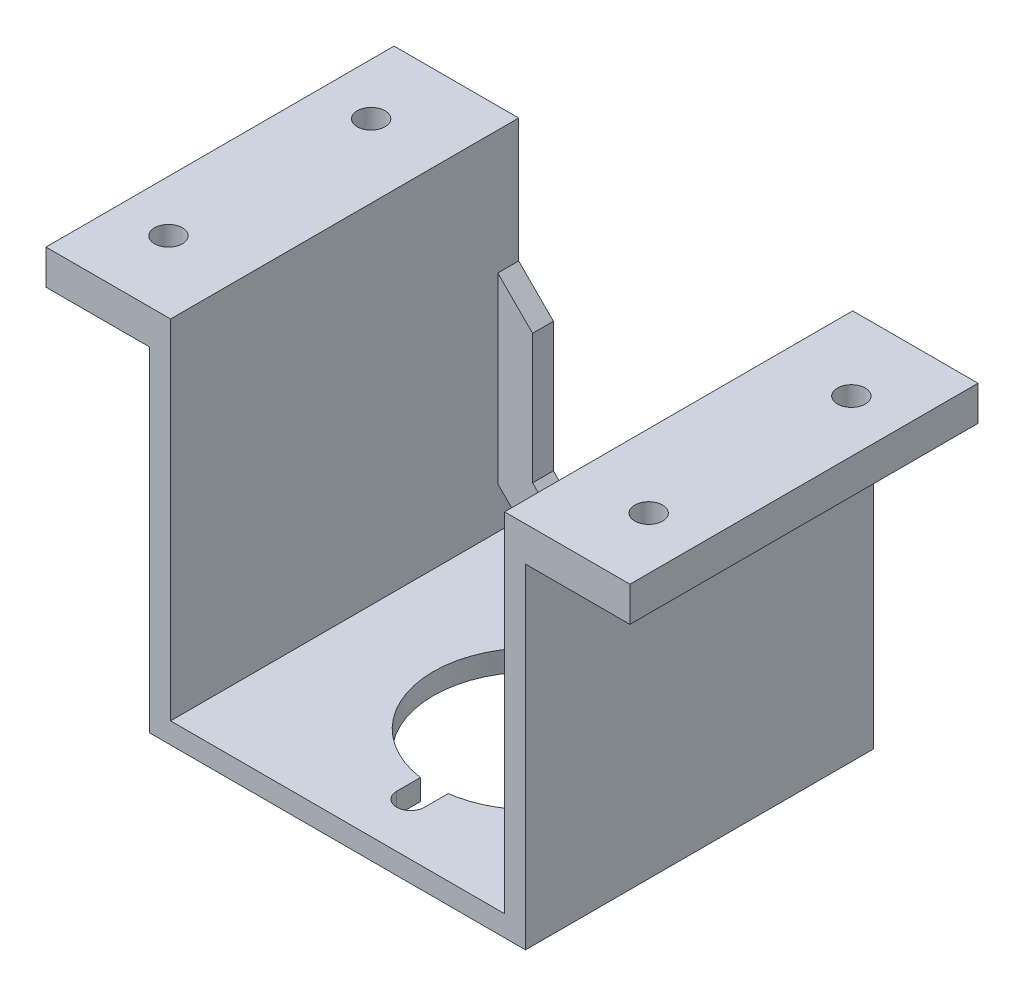
SolidWorks part; units mm, degrees
ref_plane "Front Plane" through (0, 0, 0) normal (0, 0, 1) x (1, 0, 0)
ref_plane "Top Plane" through (0, 0, 0) normal (0, 1, 0) x (1, 0, 0)
ref_plane "Right Plane" through (0, 0, 0) normal (1, 0, 0) x (0, 0, -1)
sketch "Sketch1" plane through (0, 0, 0) normal (0, 1, 0) x (1, 0, 0)
  line L1 (-23.0791, 14.3848) -> (26.9209, 14.3848)
  line L2 (-23.0791, 14.3848) -> (-23.0791, -25.6152)
  line L3 (-23.0791, -25.6152) -> (26.9209, -25.6152)
  line L4 (26.9209, 14.3848) -> (26.9209, -25.6152)
  dimension "D1" = 50
  dimension "D2" = 40
extrude "Boss-Extrude1" add sketch "Sketch1" along normal blind 3
sketch "Sketch2" plane through (0, 3, 0) normal (0, 1, 0) x (1, 0, 0)
  line L0 (-19.0791, 14.3848) -> (-19.0791, -25.6152)
  line L1 (26.9209, 14.3848) -> (-23.0791, 14.3848) construction
  line L2 (-23.0791, -25.6152) -> (26.9209, -25.6152) construction
  line L7 (-23.0791, 14.3848) -> (-23.0791, -25.6152)
  line L8 (-23.0791, -25.6152) -> (26.9209, -25.6152)
  line L9 (26.9209, -25.6152) -> (26.9209, 14.3848)
  line L10 (26.9209, 14.3848) -> (-23.0791, 14.3848)
  line L11 (-23.0791, 14.3848) -> (-23.0791, -25.6152)
  line L12 (-23.0791, -25.6152) -> (-19.0791, -25.6152)
  line L14 (-19.0791, 14.3848) -> (-23.0791, 14.3848)
  dimension "D1" = 0
  dimension "D2" = 4
sketch "Sketch5" plane through (0, 3, 0) normal (0, 1, 0) x (1, 0, 0)
  line L0 (24.9209, 14.3848) -> (24.9209, -25.6152)
  line L1 (26.9209, 14.3848) -> (-23.0791, 14.3848) construction
  line L2 (-23.0791, -25.6152) -> (26.9209, -25.6152) construction
  line L7 (-23.0791, 14.3848) -> (-23.0791, -25.6152)
  line L8 (-23.0791, -25.6152) -> (26.9209, -25.6152)
  line L9 (26.9209, -25.6152) -> (26.9209, 14.3848)
  line L10 (26.9209, 14.3848) -> (-23.0791, 14.3848)
  line L12 (24.9209, -25.6152) -> (26.9209, -25.6152)
  line L13 (26.9209, -25.6152) -> (26.9209, 14.3848)
  line L14 (26.9209, 14.3848) -> (24.9209, 14.3848)
  line L15 (-23.0791, 14.3848) -> (-23.0791, -25.6152)
  dimension "D1" = 0
  dimension "D2" = 2
sketch "Sketch6" plane through (0, 0, 0) normal (0, -1, 0) x (1, 0, 0)
  line L0 (-23.0791, 5.6152) -> (-1.0791, 5.6152)
  line L1 (-23.0791, -14.3848) -> (-23.0791, 25.6152) construction
  line L2 (6.9209, 5.6152) -> (6.9209, -11.8848)
  line L3 (-1.0791, 5.6152) -> (6.9209, 5.6152)
  line L4 (6.9209, 5.6152) -> (6.9209, 23.1152)
  line L5 (24.4209, 13.0152) -> (18.923, 13.0152)
  line L6 (6.9209, 5.6152) -> (24.4209, 5.6152)
  line L7 (24.4209, 5.6152) -> (24.4209, 13.0152)
  line L8 (24.4209, 5.6152) -> (24.4209, -1.7848)
  line L9 (24.4209, -1.7848) -> (18.923, -1.7848)
  arc A1 (18.923, 13.0152) -> (18.923, -1.7848) centre (6.9209, 5.6152) ccw
  circle A2 centre (6.9209, 23.1152) radius 2
  circle A3 centre (6.9209, -11.8848) radius 2
  dimension "D2" = 8
  dimension "D3" = 17.5
  dimension "D5" = 17.5
  dimension "D1" = 22
  dimension "D4" = 17.5
extrude "Cut-Extrude9" cut sketch "Sketch6" against normal blind 5
sketch "Sketch9" plane through (0, 0, 25.6152) normal (0, 0, 1) x (1, 0, 0)
sketch "Sketch16" plane through (24.4209, 0, 0) normal (-1, 0, 0) x (0, 0, 1)
  line L1 (13.0152, 0) -> (-1.7848, 0)
  line L2 (13.0152, 0) -> (13.0152, 3)
  line L3 (13.0152, 3) -> (-1.7848, 3)
  line L4 (-1.7848, 0) -> (-1.7848, 3)
extrude "Cut-Extrude10" cut sketch "Sketch16" against normal blind 0.5
sketch "Sketch21" plane through (0, 0, 0) normal (0, -1, 0) x (-1, 0, 0)
  circle A0 centre (-6.9209, -5.6152) radius 14.25
extrude "Cut-Extrude15" cut sketch "Sketch21" against normal blind 4
sketch "Sketch22" plane through (0, 3, 0) normal (0, 1, 0) x (1, 0, 0)
  line L0 (24.9209, 4.1848) -> (17.2661, 4.1848)
  line L1 (24.9209, -15.4152) -> (17.2661, -15.4152)
  line L2 (19.0989, 1.7848) -> (24.9209, 1.7848) construction
  line L3 (19.0989, -13.0152) -> (24.9209, -13.0152) construction
  circle A0 centre (6.9209, -5.6152) radius 15.9999
  arc A1 (19.0989, 1.7848) -> (19.0989, -13.0152) centre (6.9209, -5.6152) ccw construction
  arc M4 (19.0989, -13.0152) -> (19.0989, 1.7848) centre (6.9209, -5.6152) cw
  line M5 (19.0989, 1.7848) -> (24.9209, 1.7848)
  line M7 (24.9209, -13.0152) -> (19.0989, -13.0152)
  dimension "D1" = 2.4
  dimension "D2" = 2.4
extrude "Cut-Extrude16" cut sketch "Sketch22" against normal blind 4 contours A0 L0 M5 M4 | L1 A0 M7 M4
sketch "Sketch33" plane through (0, 3, 0) normal (0, 1, 0) x (1, 0, 0)
  line L0 (4.9209, 11.8848) -> (4.9209, -23.1152)
  line L1 (8.9209, -23.1152) -> (8.9209, 11.8848)
  line L2 (4.9209, 11.8848) -> (8.9209, 11.8848)
  line L3 (4.9209, -23.1152) -> (8.9209, -23.1152)
  circle A0 centre (6.9209, 11.8848) radius 2 construction
  circle A1 centre (6.9209, -23.1152) radius 2 construction
extrude "Cut-Extrude23" cut sketch "Sketch33" against normal blind 5
sketch "Sketch34" plane through (0, 0, -14.3848) normal (0, 0, -1) x (-1, 0, 0)
  line L0 (55, 0) -> (-55, 0) construction
  line L1 (-26.9209, 3) -> (23.066, 3)
  line L2 (-26.9209, 3) -> (-26.9209, 0)
  line L3 (-26.9209, 0) -> (23.066, 0)
  line L4 (23.066, 3) -> (23.066, 0)
extrude "Boss-Extrude2" add sketch "Sketch34" along normal blind 3
sketch "Sketch35" plane through (0, 0, 25.6152) normal (0, 0, 1) x (1, 0, 0)
  line L0 (55, 0) -> (-55, 0) construction
  line L1 (-23.0791, 3) -> (26.9209, 3)
  line L2 (-23.0791, 3) -> (-23.0791, 0)
  line L3 (-23.0791, 0) -> (26.9209, 0)
  line L4 (26.9209, 3) -> (26.9209, 0)
  line L5 (26.9209, 3) -> (26.9209, 0) construction
extrude "Boss-Extrude3" add sketch "Sketch35" along normal blind 3
sketch "Sketch36" plane through (26.9209, 0, 0) normal (1, 0, 0) x (0, 0, -1)
  line L0 (55, 0) -> (-55, 0) construction
  line L1 (-28.6152, 3) -> (17.3848, 3)
  line L2 (-28.6152, 3) -> (-28.6152, 0)
  line L3 (-28.6152, 0) -> (17.3848, 0)
  line L4 (17.3848, 3) -> (17.3848, 0)
  line L5 (17.3848, 3) -> (17.3848, 0) construction
extrude "Boss-Extrude4" add sketch "Sketch36" along normal blind 4
sketch "Sketch38" plane through (0, 3, 0) normal (0, 1, 0) x (1, 0, 0)
  line L0 (30.9209, -28.6152) -> (-23.0791, -28.6152) construction
  line L1 (30.9209, 17.3848) -> (27.9209, 17.3848)
  line L2 (30.9209, 17.3848) -> (30.9209, -28.6152)
  line L3 (30.9209, -28.6152) -> (27.9209, -28.6152)
  line L4 (27.9209, 17.3848) -> (27.9209, -28.6152)
  line L6 (-23.066, 17.3848) -> (-20.066, 17.3848)
  line L7 (-23.066, 17.3848) -> (-23.066, -28.6152)
  line L8 (-23.066, -28.6152) -> (-20.066, -28.6152)
  line L9 (-20.066, 17.3848) -> (-20.066, -28.6152)
  dimension "D1" = 3
  dimension "D2" = 3
extrude "Boss-Extrude5" add sketch "Sketch38" along normal blind 25
sketch "Sketch39" plane through (-23.066, 0, 0) normal (-1, 0, 0) x (0, 0, 1)
  line L1 (-17.3848, 28) -> (28.1507, 28)
  line L2 (-17.3848, 28) -> (-17.3848, 25)
  line L3 (-17.3848, 25) -> (28.1507, 25)
  line L4 (28.1507, 28) -> (28.1507, 25)
  dimension "D1" = 3
extrude "Boss-Extrude6" add sketch "Sketch39" along normal blind 15
sketch "Sketch40" plane through (30.9209, 0, 0) normal (1, 0, 0) x (0, 0, -1)
  line L0 (17.3848, 0) -> (17.3848, 28) construction
  line L1 (-28.6152, 28) -> (17.3848, 28)
  line L2 (-28.6152, 28) -> (-28.6152, 25)
  line L3 (-28.6152, 25) -> (17.3848, 25)
  line L4 (17.3848, 28) -> (17.3848, 25)
  dimension "D1" = 3
extrude "Boss-Extrude7" add sketch "Sketch40" along normal blind 15
sketch "Sketch41" plane through (-23.066, 0, 0) normal (-1, 0, 0) x (0, 0, 1)
  line L1 (28.6152, 28) -> (28.1507, 28)
  line L2 (28.6152, 28) -> (28.6152, 25)
  line L3 (28.6152, 25) -> (28.1507, 25)
  line L4 (28.1507, 28) -> (28.1507, 25)
extrude "Boss-Extrude8" add sketch "Sketch41" along normal blind 15
sketch "Sketch42" plane through (0, 25, 0) normal (0, -1, 0) x (1, 0, 0)
  line L0 (38.4209, 28.6152) -> (38.4209, -17.3848) construction
  line L1 (45.9209, 28.6152) -> (30.9209, 28.6152) construction
  line L2 (45.9209, -17.3848) -> (30.9209, -17.3848) construction
  line L3 (45.9209, 5.6152) -> (30.9209, -17.3848) construction
  line L4 (45.9209, 28.6152) -> (45.9209, -17.3848) construction
  line L5 (30.9209, 28.6152) -> (45.9209, 5.6152) construction
  line L6 (45.9209, 28.6152) -> (30.9209, 12.2239) construction
  line L7 (30.9209, 28.6152) -> (30.9209, -17.3848) construction
  line L8 (45.9209, -17.3848) -> (30.9209, 0) construction
  line L9 (44.2539, 0) -> (-44.2539, 0) construction
  circle A0 centre (38.4209, 20.4195) radius 2
  circle A2 centre (38.4209, -8.6924) radius 2
  dimension "D1" = 4
  dimension "D2" = 4
extrude "Cut-Extrude24" cut sketch "Sketch42" against normal blind 15 contours A0 | A2
sketch "Sketch43" plane through (0, 25, 0) normal (0, -1, 0) x (1, 0, 0)
  line L0 (-30.566, 28.6152) -> (-30.566, -17.3848) construction
  line L1 (-38.066, 28.6152) -> (-23.066, 28.6152) construction
  line L2 (-38.066, -17.3848) -> (-23.066, -17.3848) construction
  line L3 (40.4209, 20.4195) -> (-49.3024, 20.4195) construction
  line L4 (40.4209, -8.6924) -> (-52.4667, -8.6924) construction
  circle A0 centre (38.4209, 20.4195) radius 2 construction
  circle A1 centre (38.4209, -8.6924) radius 2 construction
  circle A2 centre (-30.566, 20.4195) radius 2
  circle A3 centre (-30.566, -8.6924) radius 2
  dimension "D1" = 4
extrude "Cut-Extrude25" cut sketch "Sketch43" against normal blind 15
sketch "Sketch44" plane through (0, 25, 0) normal (0, -1, 0) x (1, 0, 0)
  line L1 (-23.0791, 28.6152) -> (-38.066, 28.6152)
  line L2 (-23.0791, 28.6152) -> (-23.0791, -17.3848)
  line L3 (-23.0791, -17.3848) -> (-38.066, -17.3848)
  line L4 (-38.066, 28.6152) -> (-38.066, -17.3848)
  line L8 (-23.066, -17.3848) -> (-23.066, 28.6152)
  line L9 (-23.066, 28.6152) -> (-38.066, 28.6152)
  line L10 (-38.066, 28.6152) -> (-38.066, -17.3848)
  line L11 (-38.066, -17.3848) -> (-23.066, -17.3848)
  line L12 (-23.066, -17.3848) -> (-23.066, 28.6152)
  line L13 (-23.066, 28.6152) -> (-38.066, 28.6152)
  line L14 (-38.066, 28.6152) -> (-38.066, -17.3848)
  line L15 (-38.066, -17.3848) -> (-23.066, -17.3848)
  circle M9 centre (-30.566, 20.4195) radius 2
  circle M10 centre (-30.566, -8.6924) radius 2
  line M12 (-23.066, 28.6152) -> (-38.066, 28.6152)
  line M13 (-38.066, 28.6152) -> (-38.066, -17.3848)
  line M14 (-38.066, -17.3848) -> (-23.066, -17.3848)
  dimension "D1" = 0
extrude "Boss-Extrude10" add sketch "Sketch44" along normal blind 1 contours L2 M12 M13 M14 M10 M9
sketch "Sketch46" plane through (0, 25, 0) normal (0, -1, 0) x (1, 0, 0)
  line L1 (45.9209, 28.6152) -> (30.9209, 28.6152)
  line L2 (45.9209, 28.6152) -> (45.9209, -17.3848)
  line L3 (45.9209, -17.3848) -> (30.9209, -17.3848)
  line L4 (30.9209, 28.6152) -> (30.9209, -17.3848)
  line L8 (30.9209, 28.6152) -> (30.9209, -17.3848)
  line L9 (30.9209, -17.3848) -> (45.9209, -17.3848)
  line L10 (45.9209, -17.3848) -> (45.9209, 28.6152)
  line L11 (45.9209, 28.6152) -> (30.9209, 28.6152)
  line L12 (30.9209, 28.6152) -> (30.9209, -17.3848)
  line L13 (30.9209, -17.3848) -> (45.9209, -17.3848)
  line L14 (45.9209, -17.3848) -> (45.9209, 28.6152)
  line L15 (45.9209, 28.6152) -> (30.9209, 28.6152)
  line L16 (45.9209, 28.6152) -> (27.9209, 28.6152)
  line L17 (45.9209, -17.3848) -> (45.9209, 28.6152)
  line L18 (27.9209, -17.3848) -> (45.9209, -17.3848)
  line L19 (27.9209, 28.6152) -> (27.9209, -17.3848)
  line L20 (45.9209, 28.6152) -> (27.9209, 28.6152)
  line L21 (45.9209, -17.3848) -> (45.9209, 28.6152)
  line L22 (27.9209, -17.3848) -> (45.9209, -17.3848)
  line L23 (27.9209, 28.6152) -> (27.9209, -17.3848)
  circle M13 centre (38.4209, 20.4195) radius 2
  circle M14 centre (38.4209, -8.6924) radius 2
  line M15 (30.9209, 28.6152) -> (30.9209, -17.3848)
  line M16 (30.9209, -17.3848) -> (45.9209, -17.3848)
  line M17 (45.9209, -17.3848) -> (45.9209, 28.6152)
  line M18 (45.9209, 28.6152) -> (30.9209, 28.6152)
  dimension "D1" = 0
  dimension "D2" = 0
extrude "Boss-Extrude11" add sketch "Sketch46" along normal blind 1 contours M18 M15 M16 M17 M14 M13
sketch "Sketch47" plane through (0, 0, -17.3848) normal (0, 0, -1) x (-1, 0, 0)
  line L0 (55, 0) -> (-55, 0) construction
  line L1 (-45.9209, 28) -> (37.9603, 28)
  line L2 (-45.9209, 28) -> (-45.9209, 0)
  line L3 (-45.9209, 0) -> (37.9603, 0)
  line L4 (37.9603, 28) -> (37.9603, 0)
  line L19 (23.066, 0) -> (23.066, 25)
  line L20 (23.066, 25) -> (23.0791, 25)
  line L21 (-30.9209, 24) -> (-30.9209, 0)
  line L22 (-45.9209, 24) -> (-30.9209, 24)
  line L23 (-45.9209, 28) -> (-45.9209, 24)
  line L24 (-27.9209, 28) -> (-45.9209, 28)
  line L25 (-27.9209, 3) -> (-27.9209, 28)
  line L26 (20.066, 3) -> (-27.9209, 3)
  line L27 (20.066, 28) -> (20.066, 3)
  line L28 (38.066, 28) -> (20.066, 28)
  line L29 (23.066, 25) -> (23.0791, 25)
  line L30 (38.066, 24) -> (38.066, 28)
  line L31 (38.066, 24) -> (38.066, 28)
  line L32 (23.0791, 24) -> (38.066, 24)
  line L33 (23.066, 3) -> (23.066, 25)
  line L34 (23.0791, 3) -> (23.066, 3)
  line L35 (23.0791, 0) -> (23.0791, 3)
  line L36 (-30.9209, 0) -> (23.0791, 0)
  line L37 (-30.9209, 24) -> (-30.9209, 0)
  line L38 (-45.9209, 24) -> (-30.9209, 24)
  line L39 (-45.9209, 28) -> (-45.9209, 24)
  line L40 (-27.9209, 28) -> (-45.9209, 28)
  line L41 (-27.9209, 3) -> (-27.9209, 28)
  line L42 (20.066, 3) -> (-27.9209, 3)
  line L43 (20.066, 28) -> (20.066, 3)
  line L44 (38.066, 28) -> (20.066, 28)
  line L49 (23.066, 3) -> (23.066, 25)
  line L50 (23.0791, 3) -> (23.066, 3)
  line L51 (23.0791, 0) -> (23.0791, 3)
  line L52 (-30.9209, 0) -> (23.0791, 0)
  line L53 (23.0791, 24) -> (38.066, 24)
  line L54 (23.0791, 25) -> (23.0791, 24)
  line L55 (23.0791, 25) -> (23.0791, 24)
  line L56 (38.066, 28) -> (20.066, 28)
  line L57 (20.066, 28) -> (20.066, 3)
  line L58 (20.066, 3) -> (-27.9209, 3)
  line L59 (-27.9209, 3) -> (-27.9209, 28)
  line L60 (-27.9209, 28) -> (-45.9209, 28)
  line L61 (-45.9209, 28) -> (-45.9209, 24)
  line L62 (-45.9209, 24) -> (-30.9209, 24)
  line L63 (-30.9209, 24) -> (-30.9209, 0)
  line L64 (-30.9209, 0) -> (23.066, 0)
  line L65 (23.066, 0) -> (23.066, 25)
  line L66 (23.066, 25) -> (23.0791, 25)
  line L67 (23.066, 25) -> (23.0791, 25)
  line L68 (23.0791, 25) -> (23.0791, 24)
  line L69 (23.0791, 25) -> (23.0791, 24)
  line L70 (38.066, 28) -> (20.066, 28)
  line L71 (20.066, 28) -> (20.066, 3)
  line L72 (20.066, 3) -> (-27.9209, 3)
  line L73 (-27.9209, 3) -> (-27.9209, 28)
  line L74 (-27.9209, 28) -> (-45.9209, 28)
  line L75 (-45.9209, 28) -> (-45.9209, 24)
  line L76 (-45.9209, 24) -> (-30.9209, 24)
  line L77 (-30.9209, 24) -> (-30.9209, 0)
  line L78 (-30.9209, 0) -> (23.066, 0)
  line L79 (23.0791, 24) -> (38.066, 24)
  line L80 (23.0791, 24) -> (38.066, 24)
  line L81 (38.066, 24) -> (38.066, 28)
  line L82 (38.066, 24) -> (38.066, 28)
  line M35 (23.066, 0) -> (23.066, 25)
  line M36 (23.066, 25) -> (23.0791, 25)
  line M37 (23.0791, 25) -> (23.0791, 24)
  line M38 (23.0791, 24) -> (38.066, 24)
  line M40 (38.066, 28) -> (20.066, 28)
  line M41 (20.066, 28) -> (20.066, 3)
  line M42 (20.066, 3) -> (-27.9209, 3)
  line M43 (-27.9209, 3) -> (-27.9209, 28)
  line M44 (-27.9209, 28) -> (-45.9209, 28)
  line M45 (-45.9209, 28) -> (-45.9209, 24)
  line M46 (-45.9209, 24) -> (-30.9209, 24)
  line M47 (-30.9209, 24) -> (-30.9209, 0)
  line M48 (-30.9209, 0) -> (23.066, 0)
  dimension "D1" = 0
  dimension "D2" = 0
extrude "Boss-Extrude12" add sketch "Sketch47" along normal blind 2 contours L4 M40 M41 M42 M43 M44 M45 M46 M47 M48 M35 M36 M37 M38
sketch "Sketch48" plane through (0, 0, 28.6152) normal (0, 0, 1) x (1, 0, 0)
  line L0 (55, 0) -> (-55, 0) construction
  line L1 (-38.066, 28) -> (45.9209, 28)
  line L2 (-38.066, 28) -> (-38.066, 0)
  line L3 (-38.066, 0) -> (45.9209, 0)
  line L4 (45.9209, 28) -> (45.9209, 0)
  line L19 (-37.9603, 28) -> (-37.9603, 24)
  line L20 (-20.066, 28) -> (-37.9603, 28)
  line L21 (-20.066, 3) -> (-20.066, 28)
  line L22 (27.9209, 3) -> (-20.066, 3)
  line L23 (27.9209, 28) -> (27.9209, 3)
  line L24 (45.9209, 28) -> (27.9209, 28)
  line L25 (45.9209, 24) -> (45.9209, 28)
  line L26 (30.9209, 24) -> (45.9209, 24)
  line L27 (30.9209, 0) -> (30.9209, 24)
  line L28 (-23.066, 0) -> (30.9209, 0)
  line L29 (-23.066, 25) -> (-23.066, 0)
  line L30 (-23.0791, 25) -> (-23.066, 25)
  line L31 (-23.0791, 24) -> (-23.0791, 25)
  line L32 (-37.9603, 24) -> (-23.0791, 24)
  line L33 (-37.9603, 28) -> (-37.9603, 24)
  line L34 (-20.066, 28) -> (-37.9603, 28)
  line L35 (-20.066, 3) -> (-20.066, 28)
  line L36 (27.9209, 3) -> (-20.066, 3)
  line L37 (27.9209, 28) -> (27.9209, 3)
  line L38 (45.9209, 28) -> (27.9209, 28)
  line L39 (45.9209, 24) -> (45.9209, 28)
  line L40 (30.9209, 24) -> (45.9209, 24)
  line L41 (30.9209, 0) -> (30.9209, 24)
  line L42 (-23.066, 0) -> (30.9209, 0)
  line L43 (-23.066, 25) -> (-23.066, 0)
  line L44 (-23.0791, 25) -> (-23.066, 25)
  line L45 (-23.0791, 24) -> (-23.0791, 25)
  line L46 (-37.9603, 24) -> (-23.0791, 24)
  line M19 (30.9209, 0) -> (30.9209, 24)
  line M20 (30.9209, 24) -> (45.9209, 24)
  line M21 (45.9209, 24) -> (45.9209, 28)
  line M22 (45.9209, 28) -> (27.9209, 28)
  line M23 (27.9209, 28) -> (27.9209, 3)
  line M24 (27.9209, 3) -> (-20.066, 3)
  line M25 (-20.066, 3) -> (-20.066, 28)
  line M26 (-20.066, 28) -> (-38.066, 28)
  line M28 (-38.066, 24) -> (-23.0791, 24)
  line M29 (-23.0791, 24) -> (-23.0791, 25)
  line M30 (-23.0791, 25) -> (-23.066, 25)
  line M31 (-23.066, 25) -> (-23.066, 3)
  dimension "D1" = 0
extrude "Boss-Extrude13" add sketch "Sketch48" along normal blind 2 contours L43 L3 L33 M31 M19 M20 M21 M22 M23 M24 M25 M26 M28 M29 M30
sketch "Sketch49" plane through (0, 3, 0) normal (0, 1, 0) x (1, 0, 0)
  line L0 (27.9209, 19.3848) -> (27.9209, -30.6152) construction
  line L1 (-20.066, 19.3848) -> (27.9209, 19.3848)
  line L2 (-20.066, 19.3848) -> (-20.066, 17.3848)
  line L3 (-20.066, 17.3848) -> (27.9209, 17.3848)
  line L4 (27.9209, 19.3848) -> (27.9209, 17.3848)
  dimension "D1" = 2
extrude "Boss-Extrude14" add sketch "Sketch49" along normal blind 10
sketch "Sketch50" plane through (0, 0, -17.3848) normal (0, 0, 1) x (1, 0, 0)
  line L0 (-20.066, 13) -> (-9.8306, 2.7646)
  line L1 (27.9209, 13) -> (17.9209, 3)
  line L2 (-20.066, 3) -> (27.9209, 3) construction
  line L3 (27.9209, 13) -> (-20.066, 13)
  line L4 (-9.8306, 2.7646) -> (17.9209, 3)
extrude "Cut-Extrude26" cut sketch "Sketch50" against normal blind 10
sketch "Sketch51" plane through (0, 28, 0) normal (0, 1, 0) x (1, 0, 0)
  line L0 (45.9209, 19.3848) -> (45.9209, -30.6152) construction
  line L1 (-37.9603, 19.3848) -> (45.9209, 19.3848)
  line L2 (-37.9603, 19.3848) -> (-37.9603, -30.6152)
  line L3 (-37.9603, -30.6152) -> (45.9209, -30.6152)
  line L4 (45.9209, 19.3848) -> (45.9209, -30.6152)
  line L5 (45.9209, -30.6152) -> (30.9209, -30.6152) construction
  line L6 (30.9209, -30.6152) -> (30.9209, 19.3848) construction
  line L7 (30.9209, 19.3848) -> (45.9209, 19.3848) construction
  line L8 (-23.0791, 19.3848) -> (-23.0791, -30.6152) construction
  line L9 (-23.0791, -30.6152) -> (-37.9603, -30.6152) construction
  line L10 (-37.9603, -30.6152) -> (-37.9603, -28.6152) construction
  line L11 (-37.9603, -28.6152) -> (-38.066, -28.6152) construction
  line L12 (-38.066, -28.6152) -> (-38.066, 17.3848) construction
  line L13 (-38.066, 17.3848) -> (-37.9603, 17.3848) construction
  line L14 (-37.9603, 17.3848) -> (-37.9603, 19.3848) construction
  line L15 (-37.9603, 19.3848) -> (-23.0791, 19.3848) construction
  line L16 (45.9209, 19.3848) -> (45.9209, -30.6152)
  line L17 (45.9209, -30.6152) -> (30.9209, -30.6152)
  line L18 (30.9209, -30.6152) -> (30.9209, 19.3848)
  line L19 (30.9209, 19.3848) -> (45.9209, 19.3848)
  line L20 (-23.0791, 19.3848) -> (-23.0791, -30.6152)
  line L21 (-23.0791, -30.6152) -> (-37.9603, -30.6152)
  line L22 (-37.9603, -30.6152) -> (-37.9603, -28.6152)
  line L23 (-37.9603, -28.6152) -> (-38.066, -28.6152)
  line L24 (-38.066, -28.6152) -> (-38.066, 17.3848)
  line L25 (-38.066, 17.3848) -> (-37.9603, 17.3848)
  line L26 (-37.9603, 17.3848) -> (-37.9603, 19.3848)
  line L27 (-37.9603, 19.3848) -> (-23.0791, 19.3848)
  line L28 (27.9209, 19.3848) -> (27.9209, -30.6152) construction
  line L29 (27.9209, -30.6152) -> (45.9209, -30.6152) construction
  line L30 (45.9209, -30.6152) -> (45.9209, 19.3848) construction
  line L31 (45.9209, 19.3848) -> (27.9209, 19.3848) construction
  line L32 (-38.066, 17.3848) -> (-38.066, -28.6152) construction
  line L33 (-38.066, -28.6152) -> (-37.9603, -28.6152) construction
  line L34 (-37.9603, -28.6152) -> (-37.9603, -30.6152) construction
  line L35 (-37.9603, -30.6152) -> (-20.066, -30.6152) construction
  line L36 (-20.066, -30.6152) -> (-20.066, 19.3848) construction
  line L37 (-20.066, 19.3848) -> (-37.9603, 19.3848) construction
  line L38 (-37.9603, 19.3848) -> (-37.9603, 17.3848) construction
  line L39 (-37.9603, 17.3848) -> (-38.066, 17.3848) construction
  line L40 (27.9209, 19.3848) -> (27.9209, -30.6152)
  line L41 (27.9209, -30.6152) -> (45.9209, -30.6152)
  line L42 (45.9209, -30.6152) -> (45.9209, 19.3848)
  line L43 (45.9209, 19.3848) -> (27.9209, 19.3848)
  line L44 (-38.066, 17.3848) -> (-38.066, -28.6152)
  line L45 (-38.066, -28.6152) -> (-37.9603, -28.6152)
  line L46 (-37.9603, -28.6152) -> (-37.9603, -30.6152)
  line L47 (-37.9603, -30.6152) -> (-20.066, -30.6152)
  line L48 (-20.066, -30.6152) -> (-20.066, 19.3848)
  line L49 (-20.066, 19.3848) -> (-37.9603, 19.3848)
  line L50 (-37.9603, 19.3848) -> (-37.9603, 17.3848)
  line L51 (-37.9603, 17.3848) -> (-38.066, 17.3848)
  line L60 (-38.066, 17.3848) -> (-38.066, -28.6152)
  line L61 (-38.066, -28.6152) -> (-37.9603, -28.6152)
  line L62 (-37.9603, -28.6152) -> (-37.9603, -30.6152)
  line L63 (-37.9603, -30.6152) -> (-20.066, -30.6152)
  line L64 (-20.066, -30.6152) -> (-20.066, 19.3848)
  line L65 (-20.066, 19.3848) -> (-37.9603, 19.3848)
  line L66 (-37.9603, 19.3848) -> (-37.9603, 17.3848)
  line L67 (-37.9603, 17.3848) -> (-38.066, 17.3848)
  line L68 (-38.066, 17.3848) -> (-38.066, -28.6152)
  line L69 (-38.066, -28.6152) -> (-37.9603, -28.6152)
  line L70 (-37.9603, -28.6152) -> (-37.9603, -30.6152)
  line L71 (-37.9603, -30.6152) -> (-20.066, -30.6152)
  line L72 (-20.066, -30.6152) -> (-20.066, 19.3848)
  line L73 (-20.066, 19.3848) -> (-37.9603, 19.3848)
  line L74 (-37.9603, 19.3848) -> (-37.9603, 17.3848)
  line L75 (-37.9603, 17.3848) -> (-38.066, 17.3848)
  line L76 (-23.0791, -30.6152) -> (-23.0791, 19.3848)
  line L77 (-37.9603, -30.6152) -> (-23.0791, -30.6152)
  line L78 (-37.9603, -28.6152) -> (-37.9603, -30.6152)
  line L79 (-38.066, -28.6152) -> (-37.9603, -28.6152)
  line L80 (-38.066, 17.3848) -> (-38.066, -28.6152)
  line L81 (-37.9603, 17.3848) -> (-38.066, 17.3848)
  line L82 (-37.9603, 19.3848) -> (-37.9603, 17.3848)
  line L83 (-23.0791, 19.3848) -> (-37.9603, 19.3848)
  line L84 (-23.0791, -30.6152) -> (-23.0791, 19.3848)
  line L85 (-37.9603, -30.6152) -> (-23.0791, -30.6152)
  line L86 (-37.9603, -28.6152) -> (-37.9603, -30.6152)
  line L87 (-38.066, -28.6152) -> (-37.9603, -28.6152)
  line L88 (-38.066, 17.3848) -> (-38.066, -28.6152)
  line L89 (-37.9603, 17.3848) -> (-38.066, 17.3848)
  line L90 (-37.9603, 19.3848) -> (-37.9603, 17.3848)
  line L91 (-23.0791, 19.3848) -> (-37.9603, 19.3848)
  circle M21 centre (38.4209, -20.4195) radius 2
  circle M22 centre (38.4209, 8.6924) radius 2
  line M23 (27.9209, 19.3848) -> (27.9209, -30.6152)
  line M24 (27.9209, -30.6152) -> (45.9209, -30.6152)
  line M25 (45.9209, -30.6152) -> (45.9209, 19.3848)
  line M26 (45.9209, 19.3848) -> (27.9209, 19.3848)
  dimension "D1" = 0
  dimension "D2" = 0
extrude "Boss-Extrude15" add sketch "Sketch51" along normal blind 25 contours L18 L3 M25 M26 M22 M21 | L20 L1 L2 L3 | L3 L48 L1 L20 | L18 L1 M24 M23
sketch "Sketch53" plane through (0, 24, 0) normal (0, -1, 0) x (1, 0, 0)
  circle A0 centre (-30.566, 20.4195) radius 2
  circle A1 centre (-30.566, -8.6924) radius 2
extrude "Cut-Extrude27" cut sketch "Sketch53" against normal through all both and the other way through all
sketch "Sketch54" plane through (0, 0, 0) normal (0, -1, 0) x (-1, 0, 0)
  line L1 (37.9603, -30.6152) -> (-45.9209, -30.6152)
  line L2 (37.9603, -30.6152) -> (37.9603, 19.3848)
  line L3 (37.9603, 19.3848) -> (-45.9209, 19.3848)
  line L4 (-45.9209, -30.6152) -> (-45.9209, 19.3848)
  line L5 (23.0791, 19.3848) -> (37.9603, 19.3848)
  line L6 (23.0791, 19.3848) -> (23.0791, -30.6152)
  line L7 (23.0791, -30.6152) -> (37.9603, -30.6152)
  line L8 (37.9603, 19.3848) -> (37.9603, -30.6152)
  line L9 (-30.9209, 19.3848) -> (-45.9209, 19.3848)
  line L10 (-30.9209, 19.3848) -> (-30.9209, -30.6152)
  line L11 (-30.9209, -30.6152) -> (-45.9209, -30.6152)
  line L12 (-45.9209, 19.3848) -> (-45.9209, -30.6152)
  line M1 (23.0791, -28.6152) -> (23.0791, 14.3848)
  line M5 (-30.9209, 19.3848) -> (-30.9209, -30.6152)
extrude "Cut-Extrude28" cut sketch "Sketch54" against normal blind 48 contours L3 L6 L1 L2 M1 | L4 L1 L3 M5
sketch "Sketch55" plane through (-38.066, 0, 0) normal (-1, 0, 0) x (0, 0, 1)
  line L0 (28.6152, 24) -> (-17.3848, 24) construction
  line L1 (-17.3848, 28) -> (28.6152, 28)
  line L2 (-17.3848, 28) -> (-17.3848, 24)
  line L3 (-17.3848, 24) -> (28.6152, 24)
  line L4 (28.6152, 28) -> (28.6152, 24)
extrude "Cut-Extrude29" cut sketch "Sketch55" against normal blind 3
sketch "Sketch56" plane through (0, 0, -17.3848) normal (0, 0, 1) x (1, 0, 0)
  line L0 (-20.066, 16.6091) -> (-6.4569, 3)
  line L1 (27.9209, 3) -> (22.9209, 3)
  line L2 (27.9209, 3) -> (27.9209, 30.2183)
  line L3 (27.9209, 30.2183) -> (22.9209, 30.2183)
  line L4 (22.9209, 3) -> (22.9209, 30.2183)
  line L5 (-20.066, 3) -> (-15.066, 3)
  line L6 (-20.066, 3) -> (-20.066, 30.2183)
  line L7 (-20.066, 30.2183) -> (-15.066, 30.2183)
  line L8 (-15.066, 3) -> (-15.066, 30.2183)
  line L9 (-20.066, 3) -> (27.9209, 3)
  line L10 (-20.066, 3) -> (-20.066, 8)
  line L11 (-20.066, 8) -> (27.9209, 8)
  line L12 (27.9209, 3) -> (27.9209, 8)
  line L13 (-6.4569, 3) -> (-20.066, 3)
  line L14 (-20.066, 16.6091) -> (-20.066, 3)
  line L15 (27.9209, 16.6091) -> (14.3118, 3)
  line L16 (14.3118, 3) -> (27.9209, 3)
  line L17 (27.9209, 3) -> (27.9209, 16.6091)
  line L18 (22.9209, 30.2183) -> (27.9209, 35.2183)
  line L19 (27.9209, 35.2183) -> (27.9209, 30.2183)
  line L20 (27.9209, 30.2183) -> (22.9209, 30.2183)
  line L21 (-15.066, 30.2183) -> (-20.066, 35.2183)
  line L22 (-20.066, 35.2183) -> (-20.066, 30.2183)
  line L23 (-20.066, 30.2183) -> (-15.066, 30.2183)
  line L24 (-15.066, 30.2183) -> (-20.066, 16.6091)
  line M13 (-20.066, 3) -> (-10.066, 3)
  line M14 (-10.066, 3) -> (-20.066, 13)
  line M15 (-20.066, 13) -> (-20.066, 3)
  dimension "D1" = 5
  dimension "D2" = 5
  dimension "D3" = 5
extrude "Boss-Extrude18" add sketch "Sketch56" along normal blind 1 contours L8 L11 L0 | L11 L9 L0 M14 | L8 L0 L6 M14 | L24 L7 L6 | L8 L24 L0 | L15 L11 L0 L9 | L11 L15 L9 L4 | L4 L15 L11 | L2 L15 L4 L11 | L15 L2 L3 L4 | L21 L22 L7 | L19 L18 L3 | L11 L4 L1 L2 | L11 L6 L8 M13 | L8 M13 M14 | L11 M15 M14
sketch "Sketch57" plane through (0, 0, -17.3848) normal (0, 0, -1) x (-1, 0, 0)
  line L0 (23.0791, 3) -> (19.0791, 3) construction
  line L1 (-27.9209, 35.2183) -> (21.0791, 35.2183)
  line L2 (-27.9209, 35.2183) -> (-27.9209, 3)
  line L3 (-27.9209, 3) -> (21.0791, 3)
  line L4 (21.0791, 35.2183) -> (21.0791, 3)
  line L15 (-27.9209, 35.2183) -> (-27.9209, 3)
  line L16 (-22.9209, 30.2183) -> (-27.9209, 35.2183)
  line L17 (-22.9209, 11.6091) -> (-22.9209, 30.2183)
  line L18 (-19.3118, 8) -> (-22.9209, 11.6091)
  line L19 (11.4569, 8) -> (-19.3118, 8)
  line L20 (15.066, 11.6091) -> (11.4569, 8)
  line L21 (15.066, 30.2183) -> (15.066, 11.6091)
  line L22 (20.066, 35.2183) -> (15.066, 30.2183)
  line L23 (20.066, 3) -> (20.066, 35.2183)
  line L24 (-27.9209, 3) -> (20.066, 3)
  line L25 (-27.9209, 35.2183) -> (-27.9209, 3)
  line L26 (-22.9209, 30.2183) -> (-27.9209, 35.2183)
  line L27 (-22.9209, 11.6091) -> (-22.9209, 30.2183)
  line L28 (-19.3118, 8) -> (-22.9209, 11.6091)
  line L29 (11.4569, 8) -> (-19.3118, 8)
  line L30 (15.066, 11.6091) -> (11.4569, 8)
  line L31 (15.066, 30.2183) -> (15.066, 11.6091)
  line L32 (20.066, 35.2183) -> (15.066, 30.2183)
  line L33 (20.066, 3) -> (20.066, 35.2183)
  line L34 (-27.9209, 3) -> (20.066, 3)
  line M16 (9.8306, 2.7646) -> (20.066, 13)
  line M17 (20.066, 13) -> (20.066, 35.2183)
  line M18 (20.066, 35.2183) -> (15.066, 30.2183)
  line M19 (15.066, 30.2183) -> (15.066, 11.6091)
  line M20 (15.066, 11.6091) -> (11.4569, 8)
  line M21 (11.4569, 8) -> (-19.3118, 8)
  line M22 (-19.3118, 8) -> (-22.9209, 11.6091)
  line M23 (-22.9209, 11.6091) -> (-22.9209, 30.2183)
  line M24 (-22.9209, 30.2183) -> (-27.9209, 35.2183)
  line M25 (-27.9209, 35.2183) -> (-27.9209, 13)
  line M26 (-27.9209, 13) -> (-17.9209, 3)
  dimension "D1" = 0
extrude "Boss-Extrude19" add sketch "Sketch57" along normal up to surface (2 mm away) contours L3 M26 M16 M17 M18 M19 M20 M21 M22 M23 M24 M25 up to face at (0.5796, 30.3603, -19.3848)
sketch "Sketch58" plane through (0, 0, -16.3848) normal (0, 0, 1) x (1, 0, 0)
  line L0 (-20.066, 3) -> (-14.066, 3)
  line L1 (27.9209, 3) -> (-20.066, 3) construction
  line L2 (-14.066, 3) -> (-20.066, 9)
  line L3 (-20.066, 3) -> (-20.066, 35.2183) construction
  line L4 (-20.066, 9) -> (-20.066, 3)
  line L5 (27.9209, 3) -> (27.9209, 9)
  line L6 (27.9209, 9) -> (21.9209, 3)
  line L7 (-20.066, 3) -> (27.9209, 3) construction
  line L8 (21.9209, 3) -> (27.9209, 3)
extrude "Cut-Extrude30" cut sketch "Sketch58" against normal up to surface (3 mm away) up to face at (1.2374, 31.2046, -19.3848)
